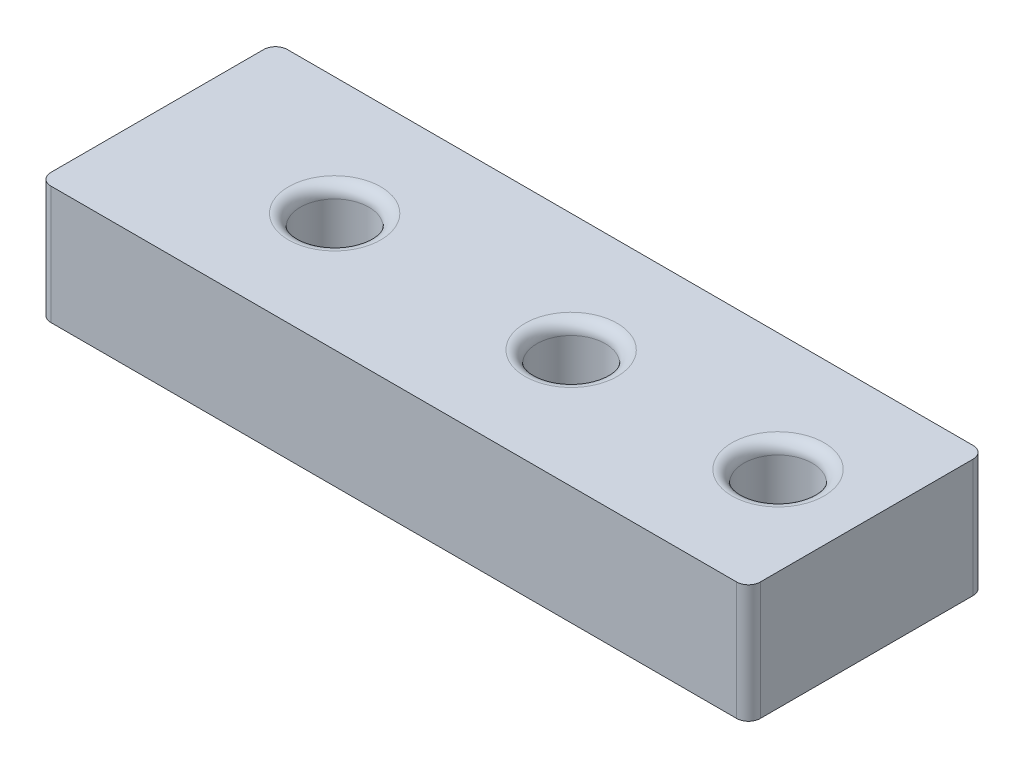
SolidWorks part; units mm, degrees
ref_plane "Front Plane" through (0, 0, 0) normal (0, 0, 1) x (1, 0, 0)
ref_plane "Top Plane" through (0, 0, 0) normal (0, 1, 0) x (1, 0, 0)
ref_plane "Right Plane" through (0, 0, 0) normal (1, 0, 0) x (0, 0, -1)
sketch "Sketch1" plane through (0, 0, 0) normal (0, 1, 0) x (1, 0, 0)
  line L1 (-38.1, 12.7) -> (38.1, 12.7)
  line L2 (-38.1, 12.7) -> (-38.1, -12.7)
  line L3 (-38.1, -12.7) -> (38.1, -12.7)
  line L4 (38.1, 12.7) -> (38.1, -12.7)
  line L5 (-38.1, 12.7) -> (38.1, -12.7) construction
  line L6 (-38.1, -12.7) -> (38.1, 12.7) construction
  point P0 (0, 0)
  dimension "D1" = 76.2
  dimension "D2" = 25.4
extrude "Boss-Extrude1" add sketch "Sketch1" along normal blind 12.7
hole_wizard "1/4 Clearance Hole1" positions "Sketch2" profile "Sketch3" hole size "1/4" standard "ANSI Inch" end condition through all
sketch "Sketch2" plane through (0, 12.7, 0) normal (0, 1, 0) x (1, 0, 0)
  line L0 (38.1, -12.7) -> (38.1, 12.7) construction
  point P0 (28.575, 0)
  point P7 (-19.05, 0)
  point P9 (6.35, 0)
  point P16 (6.35, 0)
  point P17 (0, 0)
  point P18 (0, 0)
  point P19 (0, 0)
  dimension "D1" = 9.525
  dimension "D2" = 31.75
  dimension "D3" = 25.4
sketch "Sketch3" plane through (28.575, 12.7, 0) normal (1, 0, 0) x (0, 0, 1)
  line L0 (0, 0) -> (0, 12.7)
  line L1 (0, 12.7) -> (3.683, 12.7)
  line L2 (3.683, 12.7) -> (3.683, 0)
  line L5 (3.683, 0) -> (0, 0)
  line L11 (0, -6.35) -> (0, 107.95) construction
  dimension "Thru Hole Dia." = 7.366
  dimension "Thru Hole Depth" = 12.7
fillet "Fillet1" radius 1.27 10 edges at (-19.05, 12.7, 3.683) (-19.05, 0, 3.683) (6.35, 12.7, 3.683) (6.35, 0, 3.683) (28.575, 12.7, 3.683) (28.575, 0, 3.683) (38.1, 6.35, -12.7) (38.1, 6.35, 12.7) (-38.1, 6.35, -12.7) (-38.1, 6.35, 12.7)
